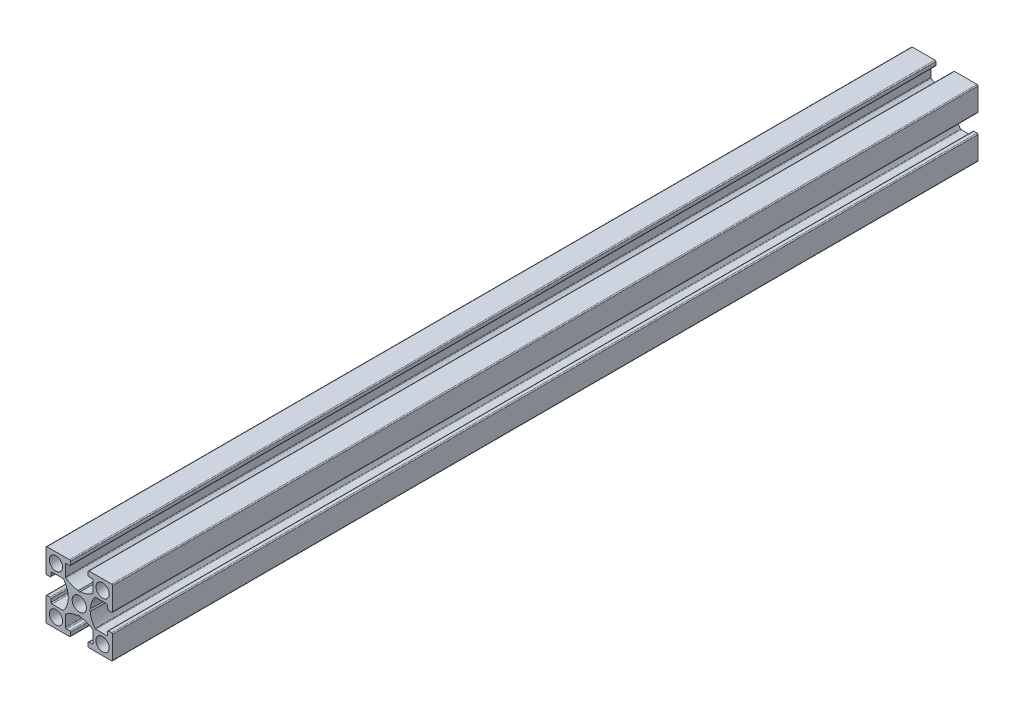
SolidWorks part; units mm, degrees
ref_plane "정면" through (0, 0, 0) normal (0, 0, 1) x (1, 0, 0)
ref_plane "윗면" through (0, 0, 0) normal (0, 1, 0) x (1, 0, 0)
ref_plane "우측면" through (0, 0, 0) normal (1, 0, 0) x (0, 0, -1)
sketch "Model" plane through (0, 0, 0) normal (0, 0, 1) x (1, 0, 0)
  line L0 (2307.7639, 1192.1343) -> (2307.7639, 1195.3915)
  line L1 (2307.4639, 1195.6915) -> (2306.5639, 1195.6915)
  line L2 (2306.2639, 1195.9915) -> (2306.2639, 1196.8915)
  line L3 (2306.5639, 1197.1915) -> (2313.3139, 1197.1915)
  line L4 (2313.6139, 1196.8915) -> (2313.6139, 1190.1415)
  line L5 (2313.3139, 1189.8415) -> (2312.4139, 1189.8415)
  line L6 (2312.1139, 1190.1415) -> (2312.1139, 1191.0415)
  line L7 (2311.8139, 1191.3415) -> (2308.5567, 1191.3415)
  line L8 (2306.9212, 1187.4988) -> (2306.6139, 1187.1915)
  line L9 (2306.6139, 1187.1915) -> (2306.9212, 1186.8843)
  line L10 (2308.5567, 1183.0415) -> (2311.8139, 1183.0415)
  line L11 (2312.1139, 1183.3415) -> (2312.1139, 1184.2415)
  line L12 (2312.4139, 1184.5415) -> (2313.3139, 1184.5415)
  line L13 (2313.6139, 1184.2415) -> (2313.6139, 1177.4915)
  line L14 (2313.3139, 1177.1915) -> (2306.5639, 1177.1915)
  line L15 (2306.2639, 1177.4915) -> (2306.2639, 1178.3915)
  line L16 (2306.5639, 1178.6915) -> (2307.4639, 1178.6915)
  line L17 (2307.7639, 1178.9915) -> (2307.7639, 1182.2488)
  line L18 (2303.9212, 1183.8843) -> (2303.6139, 1184.1915)
  line L19 (2303.6139, 1184.1915) -> (2303.3066, 1183.8843)
  line L20 (2299.4639, 1182.2488) -> (2299.4639, 1178.9915)
  line L21 (2299.7639, 1178.6915) -> (2300.6639, 1178.6915)
  line L22 (2300.9639, 1178.3915) -> (2300.9639, 1177.4915)
  line L23 (2300.6639, 1177.1915) -> (2293.9139, 1177.1915)
  line L24 (2293.6139, 1177.4915) -> (2293.6139, 1184.2415)
  line L25 (2293.9139, 1184.5415) -> (2294.8139, 1184.5415)
  line L26 (2295.1139, 1184.2415) -> (2295.1139, 1183.3415)
  line L27 (2295.4139, 1183.0415) -> (2298.6712, 1183.0415)
  line L28 (2300.3066, 1186.8843) -> (2300.6139, 1187.1915)
  line L29 (2300.6139, 1187.1915) -> (2300.3066, 1187.4988)
  line L30 (2298.6712, 1191.3415) -> (2295.4139, 1191.3415)
  line L31 (2295.1139, 1191.0415) -> (2295.1139, 1190.1415)
  line L32 (2294.8139, 1189.8415) -> (2293.9139, 1189.8415)
  line L33 (2293.6139, 1190.1415) -> (2293.6139, 1196.8915)
  line L34 (2293.9139, 1197.1915) -> (2300.6639, 1197.1915)
  line L35 (2300.9639, 1196.8915) -> (2300.9639, 1195.9915)
  line L36 (2300.6639, 1195.6915) -> (2299.7639, 1195.6915)
  line L37 (2299.4639, 1195.3915) -> (2299.4639, 1192.1343)
  line L38 (2303.3066, 1190.4988) -> (2303.6139, 1190.1915)
  line L39 (2303.6139, 1190.1915) -> (2303.9212, 1190.4988)
  circle A0 centre (2303.6139, 1187.1915) radius 2.15
  circle A1 centre (2296.6139, 1194.1915) radius 2
  circle A2 centre (2296.6139, 1180.1915) radius 2
  circle A3 centre (2310.6139, 1194.1915) radius 2
  circle A4 centre (2310.6139, 1180.1915) radius 2
  arc A5 (2307.7639, 1195.3915) -> (2307.4639, 1195.6915) centre (2307.4639, 1195.3915) ccw
  arc A6 (2306.2639, 1195.9915) -> (2306.5639, 1195.6915) centre (2306.5639, 1195.9915) ccw
  arc A7 (2306.5639, 1197.1915) -> (2306.2639, 1196.8915) centre (2306.5639, 1196.8915) ccw
  arc A8 (2313.6139, 1196.8915) -> (2313.3139, 1197.1915) centre (2313.3139, 1196.8915) ccw
  arc A9 (2313.3139, 1189.8415) -> (2313.6139, 1190.1415) centre (2313.3139, 1190.1415) ccw
  arc A10 (2312.1139, 1190.1415) -> (2312.4139, 1189.8415) centre (2312.4139, 1190.1415) ccw
  arc A11 (2312.1139, 1191.0415) -> (2311.8139, 1191.3415) centre (2311.8139, 1191.0415) ccw
  arc A12 (2308.5567, 1191.3415) -> (2308.3217, 1191.2281) centre (2308.5567, 1191.0415) ccw
  arc A13 (2308.3217, 1191.2281) -> (2306.9212, 1187.4988) centre (2313.4048, 1187.1915) ccw
  arc A14 (2306.9212, 1186.8843) -> (2308.3217, 1183.155) centre (2313.4048, 1187.1915) ccw
  arc A15 (2308.3217, 1183.155) -> (2308.5567, 1183.0415) centre (2308.5567, 1183.3415) ccw
  arc A16 (2311.8139, 1183.0415) -> (2312.1139, 1183.3415) centre (2311.8139, 1183.3415) ccw
  arc A17 (2312.4139, 1184.5415) -> (2312.1139, 1184.2415) centre (2312.4139, 1184.2415) ccw
  arc A18 (2313.6139, 1184.2415) -> (2313.3139, 1184.5415) centre (2313.3139, 1184.2415) ccw
  arc A19 (2313.3139, 1177.1915) -> (2313.6139, 1177.4915) centre (2313.3139, 1177.4915) ccw
  arc A20 (2306.2639, 1177.4915) -> (2306.5639, 1177.1915) centre (2306.5639, 1177.4915) ccw
  arc A21 (2306.5639, 1178.6915) -> (2306.2639, 1178.3915) centre (2306.5639, 1178.3915) ccw
  arc A22 (2307.4639, 1178.6915) -> (2307.7639, 1178.9915) centre (2307.4639, 1178.9915) ccw
  arc A23 (2307.7639, 1182.2488) -> (2307.6505, 1182.4837) centre (2307.4639, 1182.2488) ccw
  arc A24 (2307.6505, 1182.4837) -> (2303.9212, 1183.8843) centre (2303.6139, 1177.4007) ccw
  arc A25 (2303.3066, 1183.8843) -> (2299.5774, 1182.4837) centre (2303.6139, 1177.4007) ccw
  arc A26 (2299.5774, 1182.4837) -> (2299.4639, 1182.2488) centre (2299.7639, 1182.2488) ccw
  arc A27 (2299.4639, 1178.9915) -> (2299.7639, 1178.6915) centre (2299.7639, 1178.9915) ccw
  arc A28 (2300.9639, 1178.3915) -> (2300.6639, 1178.6915) centre (2300.6639, 1178.3915) ccw
  arc A29 (2300.6639, 1177.1915) -> (2300.9639, 1177.4915) centre (2300.6639, 1177.4915) ccw
  arc A30 (2293.6139, 1177.4915) -> (2293.9139, 1177.1915) centre (2293.9139, 1177.4915) ccw
  arc A31 (2293.9139, 1184.5415) -> (2293.6139, 1184.2415) centre (2293.9139, 1184.2415) ccw
  arc A32 (2295.1139, 1184.2415) -> (2294.8139, 1184.5415) centre (2294.8139, 1184.2415) ccw
  arc A33 (2295.1139, 1183.3415) -> (2295.4139, 1183.0415) centre (2295.4139, 1183.3415) ccw
  arc A34 (2298.6712, 1183.0415) -> (2298.9061, 1183.155) centre (2298.6712, 1183.3415) ccw
  arc A35 (2298.9061, 1183.155) -> (2300.3066, 1186.8843) centre (2293.8231, 1187.1915) ccw
  arc A36 (2300.3066, 1187.4988) -> (2298.9061, 1191.2281) centre (2293.8231, 1187.1915) ccw
  arc A37 (2298.9061, 1191.2281) -> (2298.6712, 1191.3415) centre (2298.6712, 1191.0415) ccw
  arc A38 (2295.4139, 1191.3415) -> (2295.1139, 1191.0415) centre (2295.4139, 1191.0415) ccw
  arc A39 (2294.8139, 1189.8415) -> (2295.1139, 1190.1415) centre (2294.8139, 1190.1415) ccw
  arc A40 (2293.6139, 1190.1415) -> (2293.9139, 1189.8415) centre (2293.9139, 1190.1415) ccw
  arc A41 (2293.9139, 1197.1915) -> (2293.6139, 1196.8915) centre (2293.9139, 1196.8915) ccw
  arc A42 (2300.9639, 1196.8915) -> (2300.6639, 1197.1915) centre (2300.6639, 1196.8915) ccw
  arc A43 (2300.6639, 1195.6915) -> (2300.9639, 1195.9915) centre (2300.6639, 1195.9915) ccw
  arc A44 (2299.7639, 1195.6915) -> (2299.4639, 1195.3915) centre (2299.7639, 1195.3915) ccw
  arc A45 (2299.4639, 1192.1343) -> (2299.5774, 1191.8994) centre (2299.7639, 1192.1343) ccw
  arc A46 (2299.5774, 1191.8994) -> (2303.3066, 1190.4988) centre (2303.6139, 1196.9824) ccw
  arc A47 (2303.9212, 1190.4988) -> (2307.6505, 1191.8994) centre (2303.6139, 1196.9824) ccw
  arc A48 (2307.6505, 1191.8994) -> (2307.7639, 1192.1343) centre (2307.4639, 1192.1343) ccw
extrude "보스-돌출1" add sketch "Model" along normal blind 260
extrude "컷-돌출1" cut sketch "스케치1" against normal through all
sketch "스케치1" plane through (2294.5877, 1173.1915, -764.328) normal (0, -1, 0) x (0, 0, 1)
  circle A1 centre (1034.328, 255.9738) radius 2.5
  circle A2 centre (1034.328, 55.9738) radius 2.5
  circle A4 centre (864.328, -9.0262) radius 2.5
  circle A5 centre (814.328, -9.0262) radius 2.5
  circle A6 centre (864.328, 320.9738) radius 2.5
  circle A7 centre (814.328, 320.9738) radius 2.5
  circle A8 centre (1034.328, 290.9738) radius 2.5
  circle A9 centre (1034.328, 20.9738) radius 2.5
  circle A10 centre (934.328, 320.9738) radius 2.5
  circle A11 centre (934.328, -9.0262) radius 2.5
  circle A12 centre (1034.328, 88.9738) radius 2.5
  circle A13 centre (1034.328, 222.9738) radius 2.5
extrude "컷-돌출3" cut sketch "스케치3" against normal through all
sketch "스케치3" plane through (1982.6401, 1173.1915, 1024.328) normal (0, -1, 0) x (0, 0, -1)
  circle A1 centre (1034.328, 255.9738) radius 2.5
  circle A2 centre (1034.328, 55.9738) radius 2.5
  circle A4 centre (864.328, -9.0262) radius 2.5
  circle A5 centre (814.328, -9.0262) radius 2.5
  circle A6 centre (864.328, 320.9738) radius 2.5
  circle A7 centre (814.328, 320.9738) radius 2.5
  circle A8 centre (1034.328, 290.9738) radius 2.5
  circle A9 centre (1034.328, 20.9738) radius 2.5
  circle A10 centre (934.328, 320.9738) radius 2.5
  circle A11 centre (934.328, -9.0262) radius 2.5
  circle A12 centre (1034.328, 88.9738) radius 2.5
  circle A13 centre (1034.328, 222.9738) radius 2.5
